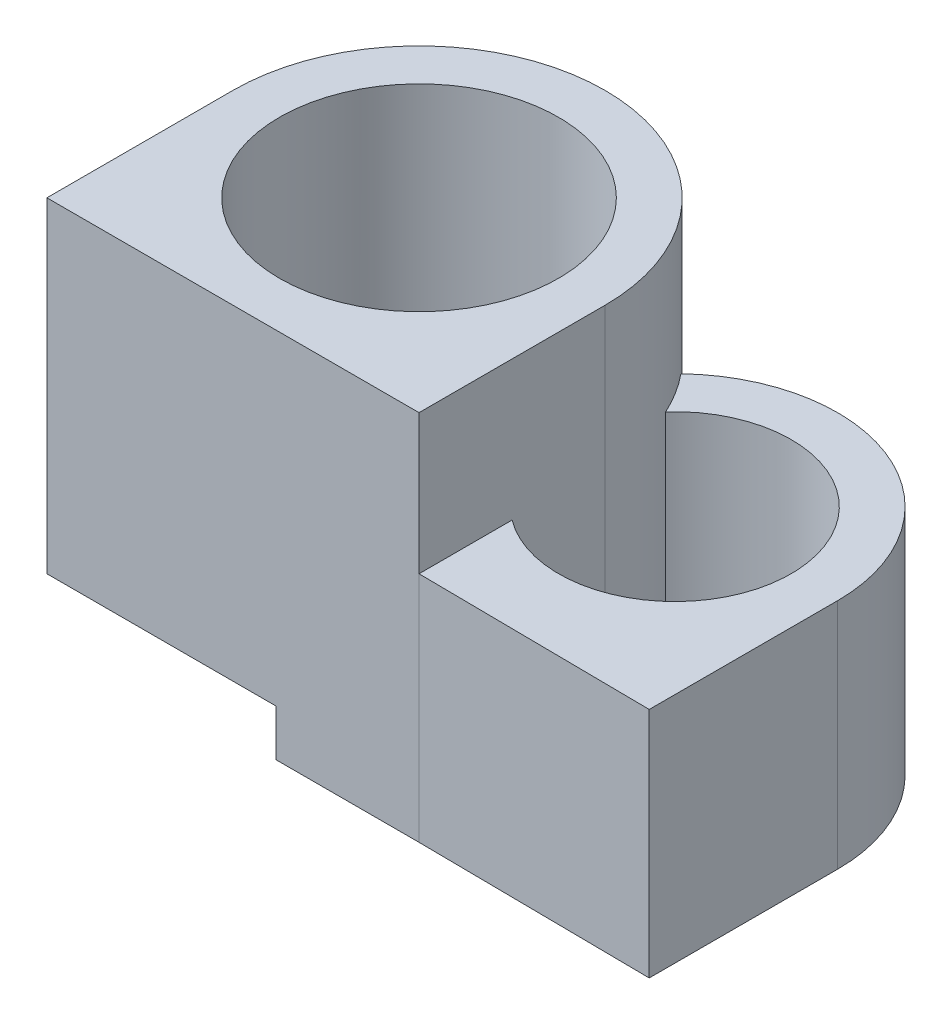
SolidWorks part; units mm, degrees
ref_plane "Front Plane" through (0, 0, 0) normal (0, 0, 1) x (1, 0, 0)
ref_plane "Top Plane" through (0, 0, 0) normal (0, 1, 0) x (1, 0, 0)
ref_plane "Right Plane" through (0, 0, 0) normal (1, 0, 0) x (0, 0, -1)
sketch "Sketch1" plane through (0, 0, 0) normal (0, 1, 0) x (1, 0, 0)
  line L1 (4, 0) -> (4, -4)
  line L2 (4, -4) -> (-4, -4)
  line L3 (-4, -4) -> (-4, 0)
  circle A0 centre (0, 0) radius 3
  arc A1 (4, 0) -> (-4, 0) centre (0, 0) ccw
  dimension "D1" = 6
  dimension "D2" = 8
extrude "Boss-Extrude1" add sketch "Sketch1" along normal blind 7
sketch "Sketch4" plane through (0, 0, 0) normal (0, -1, 0) x (1, 0, 0)
  line L0 (4, 4) -> (0.9246, 4)
  line L1 (-4, 4) -> (4, 4) construction
  line L2 (0.9246, 4) -> (0.9246, -3.8917)
  line L3 (0.9246, 4) -> (4, 4)
  line L4 (4, 0) -> (0.9246, -3.8917)
  line L5 (4, 4) -> (4, 0) construction
  arc A0 (-4, 0) -> (4, 0) centre (0, 0) ccw construction
  line M3 (4, 0) -> (4, 4)
  line M4 (4, 4) -> (-4, 4)
  circle M5 centre (0, 0) radius 3
extrude "Boss-Extrude2" add sketch "Sketch4" along normal blind 1 contours L4 L2 M3 M4 M5
sketch "Sketch5" plane through (0, -1, 0) normal (0, -1, 0) x (1, 0, 0)
  line L0 (0.9246, -2.854) -> (0.9246, 2.854)
  arc A0 (0.9246, -2.854) -> (0.9246, 2.854) centre (0, 0) ccw
sketch "Sketch6" plane through (0, -1, 0) normal (0, -1, 0) x (1, 0, 0)
  line L0 (0, 0) -> (5.5, 0)
  line L1 (9, 0) -> (9, 4.0515)
  line L2 (9, 4.0515) -> (4, 4)
  line L3 (2, 0) -> (2, 4)
  line L4 (4, 4) -> (0.9246, 4) construction
  line L5 (2, 4) -> (4, 4)
  circle A0 centre (5.5, 0) radius 2.5
  arc A1 (2, 0) -> (9, 0) centre (5.5, 0) ccw
  line M2 (0.9246, -3.8917) -> (4, 0)
  line M3 (4, 0) -> (4, 4)
  dimension "D2" = 5
  dimension "D3" = 7
  dimension "D1" = 5.5
extrude "Boss-Extrude6" add sketch "Sketch6" against normal blind 5 contours A1 L1 L2 A0 M2 M3
